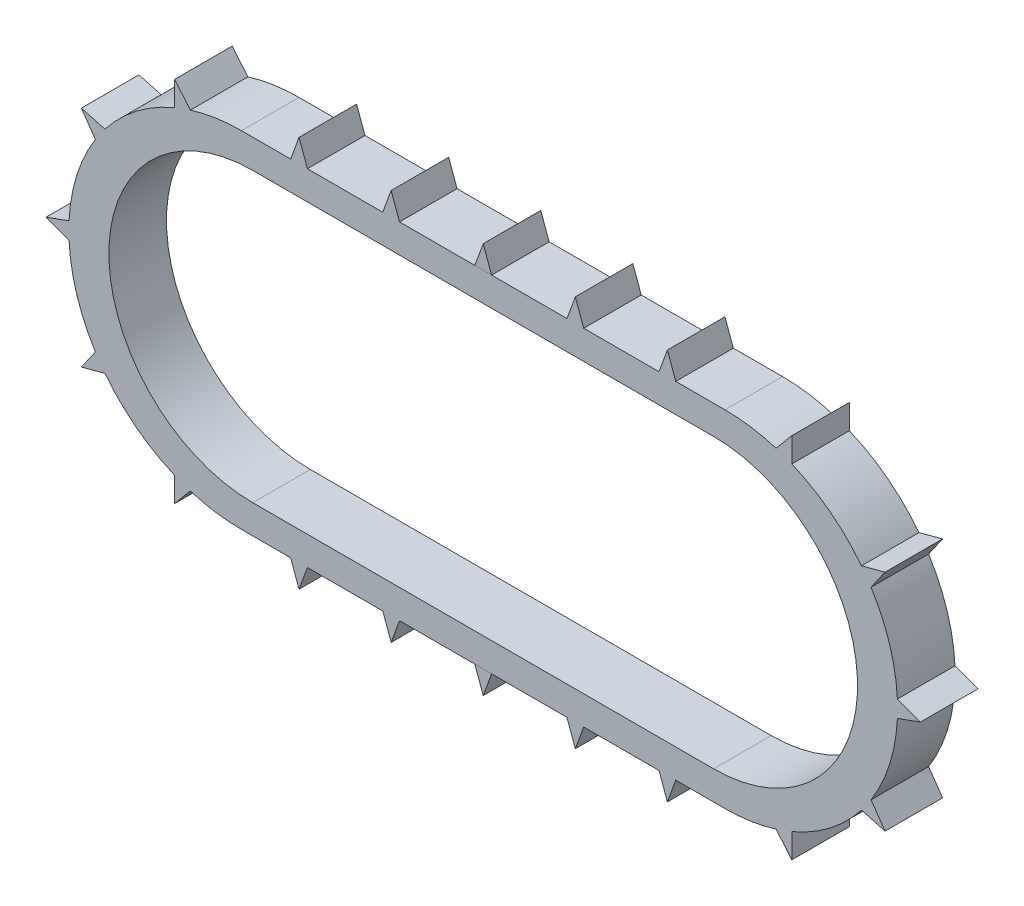
SolidWorks part; units mm, degrees
ref_plane "Front Plane" through (0, 0, 0) normal (0, 0, 1) x (1, 0, 0)
ref_plane "Top Plane" through (0, 0, 0) normal (0, 1, 0) x (1, 0, 0)
ref_plane "Right Plane" through (0, 0, 0) normal (1, 0, 0) x (0, 0, -1)
sketch "Sketch1" plane through (0, 0, 0) normal (0, 0, 1) x (1, 0, 0)
  line L0 (-210, 0) -> (210, 0) construction
  line L1 (-210, 150) -> (210, 150)
  line L2 (-210, -150) -> (210, -150)
  arc A0 (-210, 150) -> (-210, -150) centre (-210, 0) ccw
  arc A1 (210, -150) -> (210, 150) centre (210, 0) ccw
  point P2 (0, 0)
  dimension "D1" = 150
  dimension "D2" = 420
extrude "Boss-Extrude1" add sketch "Sketch1" along normal blind 50
sketch "Sketch2" plane through (0, 0, 50) normal (0, 0, 1) x (1, 0, 0)
  line L0 (200.1935, 0) -> (-200.1935, 0) construction
  line L1 (200.1935, -125) -> (-200.1935, -125)
  line L2 (200.1935, 125) -> (-200.1935, 125)
  arc A0 (200.1935, -125) -> (200.1935, 125) centre (200.1935, 0) ccw
  arc A1 (-200.1935, 125) -> (-200.1935, -125) centre (-200.1935, 0) ccw
  point P3 (0, 0)
  dimension "D1" = 125
  dimension "D2" = 400.387
extrude "Cut-Extrude1" cut sketch "Sketch2" against normal blind 50
sketch "Sketch3" plane through (0, 0, 0) normal (0, 0, 1) x (1, 0, 0)
  line L0 (-7.2794, 150) -> (0, 170)
  line L1 (210, 150) -> (-210, 150) construction
  line L4 (0, 170) -> (7.2794, 150)
  line L5 (-7.2794, 150) -> (7.2794, 150)
  line L6 (-243.9692, 0) -> (152.4807, 0) construction
  line L7 (0, -39.7005) -> (0, 226.9453) construction
  line L8 (7.2794, -150) -> (0, -170)
  line L9 (0, -170) -> (-7.2794, -150)
  line L10 (7.2794, -150) -> (-7.2794, -150)
  dimension "D1" = 110
  dimension "D2" = 110
  dimension "D3" = 20
extrude "Boss-Extrude2" add sketch "Sketch3" along normal blind 50 separate body
pattern_linear "LPattern1" count 4 spacing 80 along (1, 0, 0) of "Boss-Extrude2"
pattern_linear "LPattern2" count 4 spacing 80 along (-1, 0, 0) of "Boss-Extrude2"
sketch "Sketch4" plane through (0, 0, 50) normal (0, 0, 1) x (1, 0, 0)
  line L0 (359.8233, 7.2794) -> (379.8233, 0)
  line L1 (379.8233, 0) -> (359.8233, -7.2794)
  line L2 (359.8233, 7.2794) -> (359.8233, -7.2794)
  arc A0 (210, -150) -> (210, 150) centre (210, 0) ccw construction
  dimension "D1" = 110
  dimension "D2" = 110
  dimension "D3" = 20
extrude "Boss-Extrude3" add sketch "Sketch4" against normal blind 50
pattern_circular "CirPattern1" count 3 every 35 about axis through (210, 0, 0) along (0, 0, 1) of "Boss-Extrude3"
pattern_circular "CirPattern2" count 3 every 35 about axis through (210, 0, 0) along (0, 0, 1) of "Boss-Extrude3"
mirror "Mirror1" about plane through (0, 0, 0) normal (1, 0, 0) of "Boss-Extrude3", "CirPattern2", "CirPattern1"
